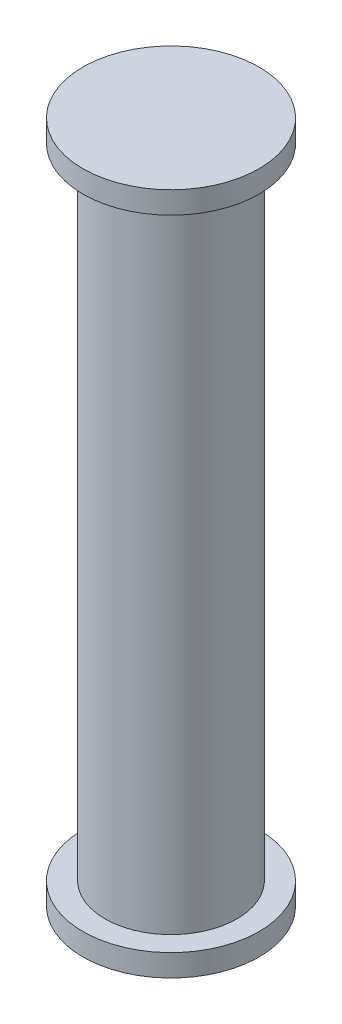
SolidWorks part; units mm, degrees
material "Titanium"
ref_plane "Front Plane" through (0, 0, 0) normal (0, 0, 1) x (1, 0, 0)
ref_plane "Top Plane" through (0, 0, 0) normal (0, 1, 0) x (1, 0, 0)
ref_plane "Right Plane" through (0, 0, 0) normal (1, 0, 0) x (0, 0, -1)
sketch "Sketch1" plane through (0, 0, 0) normal (0, 1, 0) x (1, 0, 0)
  circle A0 centre (0, 0) radius 3
extrude "Boss-Extrude1" add sketch "Sketch1" against normal blind 30
sketch "Sketch2" plane through (0, 0, 0) normal (0, 1, 0) x (1, 0, 0)
  circle A0 centre (0, 0) radius 4
extrude "Boss-Extrude2" add sketch "Sketch2" against normal blind 1
sketch "Sketch3" plane through (0, -30, 0) normal (0, -1, 0) x (1, 0, 0)
  circle A0 centre (0, 0) radius 4
extrude "Boss-Extrude3" add sketch "Sketch3" along normal blind 1
